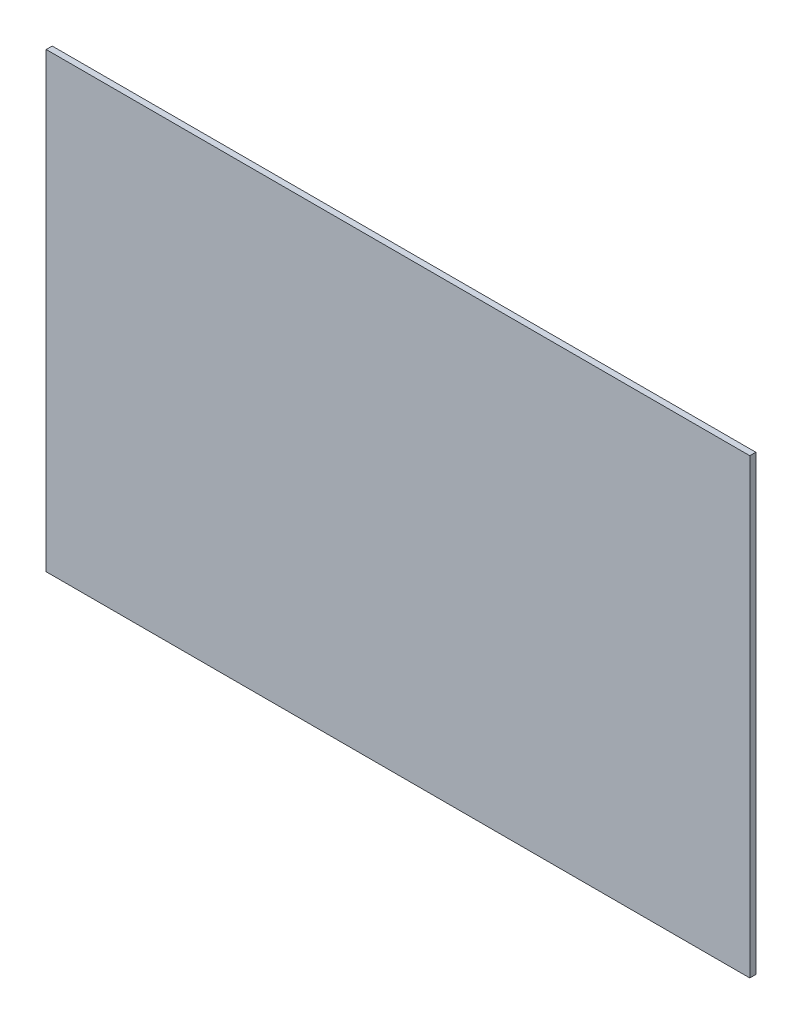
SolidWorks part; units mm, degrees
ref_plane "Front Plane" through (0, 0, 0) normal (0, 0, 1) x (1, 0, 0)
ref_plane "Top Plane" through (0, 0, 0) normal (0, 1, 0) x (1, 0, 0)
ref_plane "Right Plane" through (0, 0, 0) normal (1, 0, 0) x (0, 0, -1)
sketch "Sketch1" plane through (0, 0, 0) normal (0, 0, 1) x (1, 0, 0)
  line L1 (140, 90) -> (-140, 90)
  line L2 (140, 90) -> (140, -90)
  line L3 (140, -90) -> (-140, -90)
  line L4 (-140, 90) -> (-140, -90)
  line L5 (140, 90) -> (-140, -90) construction
  line L6 (140, -90) -> (-140, 90) construction
  point P0 (0, 0)
extrude "Boss-Extrude1" add sketch "Sketch1" along normal blind 2.4
